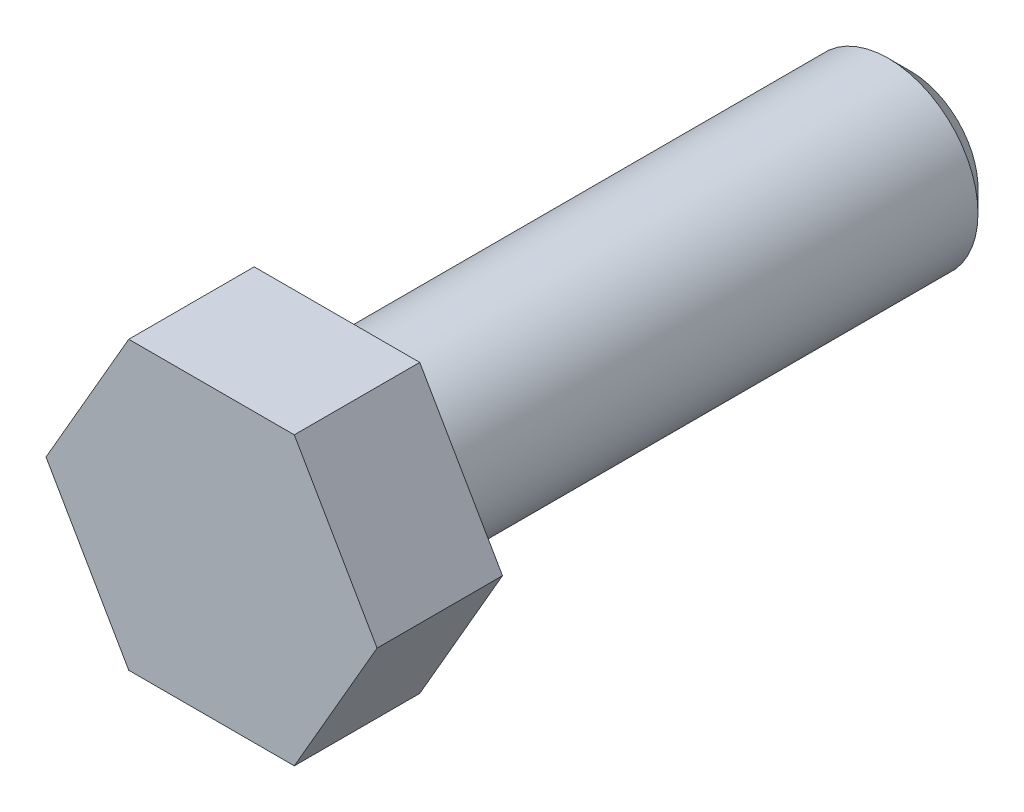
SolidWorks part; units mm, degrees
ref_plane "Plane1" through (0, 0, 0) normal (0, 0, 1) x (1, 0, 0)
ref_plane "MSC_PF1" through (0, 0, 0) normal (0, 1, 0) x (1, 0, 0)
ref_plane "Plane3" through (0, 0, 0) normal (1, 0, 0) x (0, 0, -1)
sketch "Sketch1" plane through (0, 0, 0) normal (0, 0, 1) x (1, 0, 0)
  line L0 (0, 0) -> (1, 0) construction
  line L1 (-2.3094, 4) -> (2.3094, 4)
  line L2 (-2.3094, -4) -> (2.3094, -4)
  line L3 (2.3094, 4) -> (4.6188, 0)
  line L4 (4.6188, 0) -> (2.3094, -4)
  line L5 (-2.3094, 4) -> (-4.6188, 0)
  line L6 (-4.6188, 0) -> (-2.3094, -4)
  circle A0 centre (0, 0) radius 4 construction
  dimension "P" = 1
  dimension "s" = 8
extrude "Base-Extrude" add sketch "Sketch1" along normal blind 3.5
sketch "Sketch3" plane through (0, 0, 0) normal (0, 0, -1) x (-1, 0, 0)
  circle A0 centre (0, 0) radius 2.5
  dimension "_d" = 5
extrude "Boss-Extrude1" add sketch "Sketch3" along normal blind 16
cosmetic thread "Условное изображение резьбы2"
chamfer "Chamfer1" distance 0.6134 angle 45 1 edges at (-2.5, 0, -16)
fillet "Fillet1" radius 0.25 1 edges at (2.5, 0, 0)
